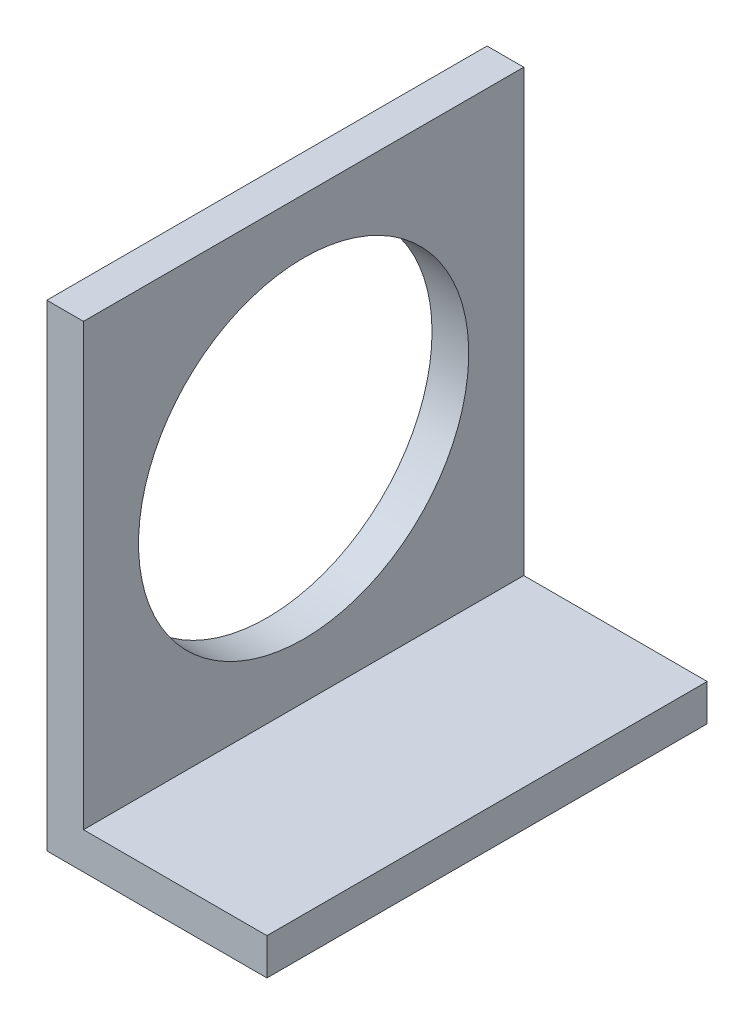
SolidWorks part; units mm, degrees
ref_plane "Front Plane" through (0, 0, 0) normal (0, 0, 1) x (1, 0, 0)
ref_plane "Top Plane" through (0, 0, 0) normal (0, 1, 0) x (1, 0, 0)
ref_plane "Right Plane" through (0, 0, 0) normal (1, 0, 0) x (0, 0, -1)
sketch "Sketch7" plane through (0, 0, 0) normal (0, 0, 1) x (1, 0, 0)
  line L0 (0, 0) -> (0, 65)
  line L1 (0, 65) -> (5, 65)
  line L2 (5, 65) -> (5, 5)
  line L3 (5, 5) -> (30, 5)
  line L4 (30, 5) -> (30, 0)
  line L5 (30, 0) -> (0, 0)
  dimension "D1" = 60
  dimension "D2" = 5
  dimension "D3" = 5
  dimension "D4" = 25
extrude "Boss-Extrude1" add sketch "Sketch7" along normal blind 60
sketch "Sketch8" plane through (5, 0, 0) normal (1, 0, 0) x (0, 0, -1)
  circle A0 centre (-30, 35) radius 22.5
  dimension "D1" = 45
extrude "Cut-Extrude1" cut sketch "Sketch8" against normal blind 60
